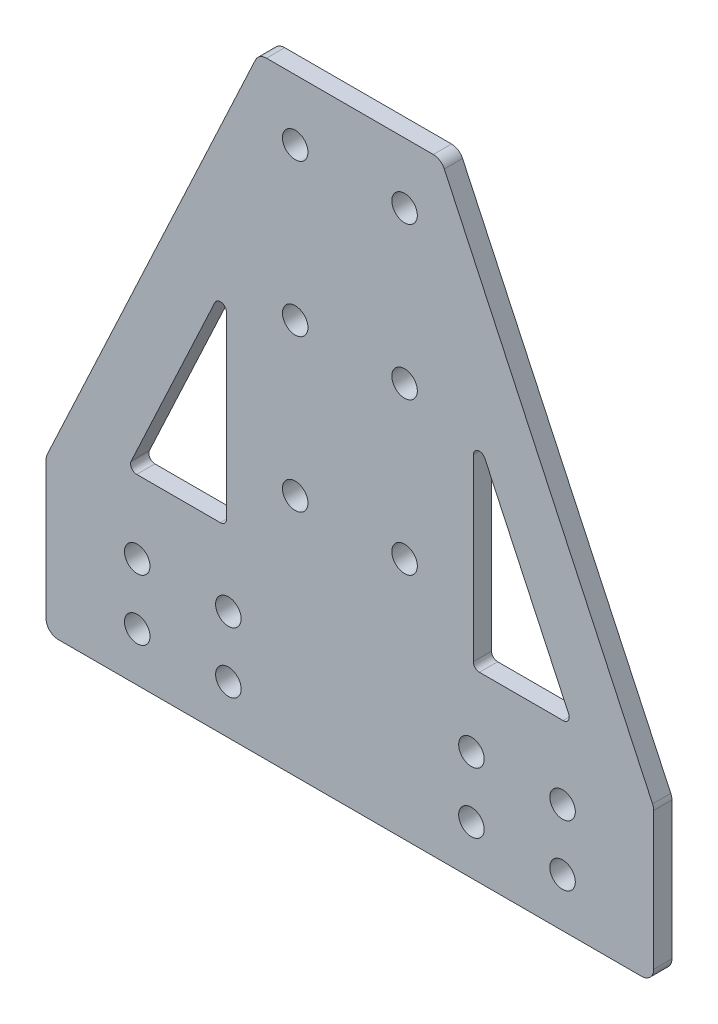
SolidWorks part; units mm, degrees
material "Thornel Mat VMA"
ref_plane "Front" through (0, 0, 0) normal (0, 0, 1) x (1, 0, 0)
ref_plane "Top" through (0, 0, 0) normal (0, 1, 0) x (1, 0, 0)
ref_plane "Right" through (0, 0, 0) normal (1, 0, 0) x (0, 0, -1)
sketch "草图1" plane through (0, 0, 0) normal (0, 0, 1) x (1, 0, 0)
  line L3 (-15, 45.2299) -> (15, 45.2299)
  line L5 (0, 0) -> (15, 45.2299) construction
  line L6 (-15, 45.2299) -> (0, 0) construction
  line L9 (-50, -54.7701) -> (50, -54.7701)
  line L13 (-15, 45.2299) -> (-50, -29.684)
  line L14 (15, 45.2299) -> (50, -29.684)
  line L15 (-50, -29.684) -> (-50, -54.7701)
  line L16 (50, -29.684) -> (50, -54.7701)
  point P0 (0, 0)
  dimension "D1" = 30
  dimension "D2" = 100
  dimension "D3" = 100
extrude "凸台-拉伸1" add sketch "草图1" along normal blind 3 contours L13 L15 L9 L16 L14 L3
sketch "草图2" plane through (0, 0, 3) normal (0, 0, 1) x (1, 0, 0)
  line L0 (0, 45.2299) -> (0, 11.5174) construction
  line L1 (-15, 45.2299) -> (15, 45.2299) construction
  line L2 (-50, -54.7701) -> (50, -54.7701) construction
  line L4 (0, -54.7701) -> (0, -12.6609) construction
  line L5 (-50, -54.7701) -> (50, -54.7701) construction
  line L6 (-9, 35.2299) -> (9, 35.2299) construction
  line L7 (-20.3145, 5.7271) -> (-20.3145, -23.7701)
  line L8 (-21.3145, -24.7701) -> (-35.0957, -24.7701)
  line L9 (-36.0017, -23.3468) -> (-22.2205, 6.1504)
  line L10 (-15, 45.2299) -> (-50, -29.684) construction
  line L11 (36.0017, -23.3468) -> (22.2205, 6.1504)
  line L12 (21.3145, -24.7701) -> (35.0957, -24.7701)
  line L13 (20.3145, 5.7271) -> (20.3145, -23.7701)
  circle A0 centre (-9, 35.2299) radius 2.1
  circle A1 centre (9, 35.2299) radius 2.1
  circle A2 centre (9, 10.2299) radius 2.1
  circle A3 centre (-9, 10.2299) radius 2.1
  circle A4 centre (-20, -36.7701) radius 2.1
  circle A5 centre (-20, -46.7701) radius 2.1
  circle A6 centre (20, -46.7701) radius 2.1
  circle A7 centre (20, -36.7701) radius 2.1
  circle A9 centre (-9, -14.7701) radius 2.1
  circle A10 centre (9, -14.7701) radius 2.1
  circle A11 centre (-35, -36.7701) radius 2.1
  circle A12 centre (-35, -46.7701) radius 2.1
  circle A13 centre (35, -36.7701) radius 2.1
  circle A14 centre (35, -46.7701) radius 2.1
  arc A15 (-21.3145, -24.7701) -> (-20.3145, -23.7701) centre (-21.3145, -23.7701) ccw
  arc A16 (-35.0957, -24.7701) -> (-36.0017, -23.3468) centre (-35.0957, -23.7701) cw
  arc A17 (-20.3145, 5.7271) -> (-22.2205, 6.1504) centre (-21.3145, 5.7271) ccw
  arc A18 (20.3145, 5.7271) -> (22.2205, 6.1504) centre (21.3145, 5.7271) cw
  arc A19 (35.0957, -24.7701) -> (36.0017, -23.3468) centre (35.0957, -23.7701) ccw
  arc A20 (21.3145, -24.7701) -> (20.3145, -23.7701) centre (21.3145, -23.7701) cw
  point P17 (0, 35.2299)
  point P48 (-20.3145, -24.7701)
  point P53 (-20.3145, 10.2299)
  point P63 (20.3145, 10.2299)
  point P64 (20.3145, -24.7701)
  dimension "D1" = 4.2
  dimension "D7" = 15
  dimension "D8" = 4.2
  dimension "D14" = 1
  dimension "D15" = 25
  dimension "D2" = 18
  dimension "D5" = 10
  dimension "D6" = 8
  dimension "D9" = 40
  dimension "D10" = 10
  dimension "D11" = 35
  dimension "D12" = 10
  dimension "D13" = 35
  dimension "D3" = 2
  dimension "D4" = 3
extrude "切除-拉伸2" cut sketch "草图2" against normal up to next
fillet "圆角1" radius 2 6 edges at (15, 45.2299, 1.5) (50, -29.684, 1.5) (-50, -29.684, 1.5) (-50, -54.7701, 1.5) (50, -54.7701, 1.5) (-15, 45.2299, 1.5)
